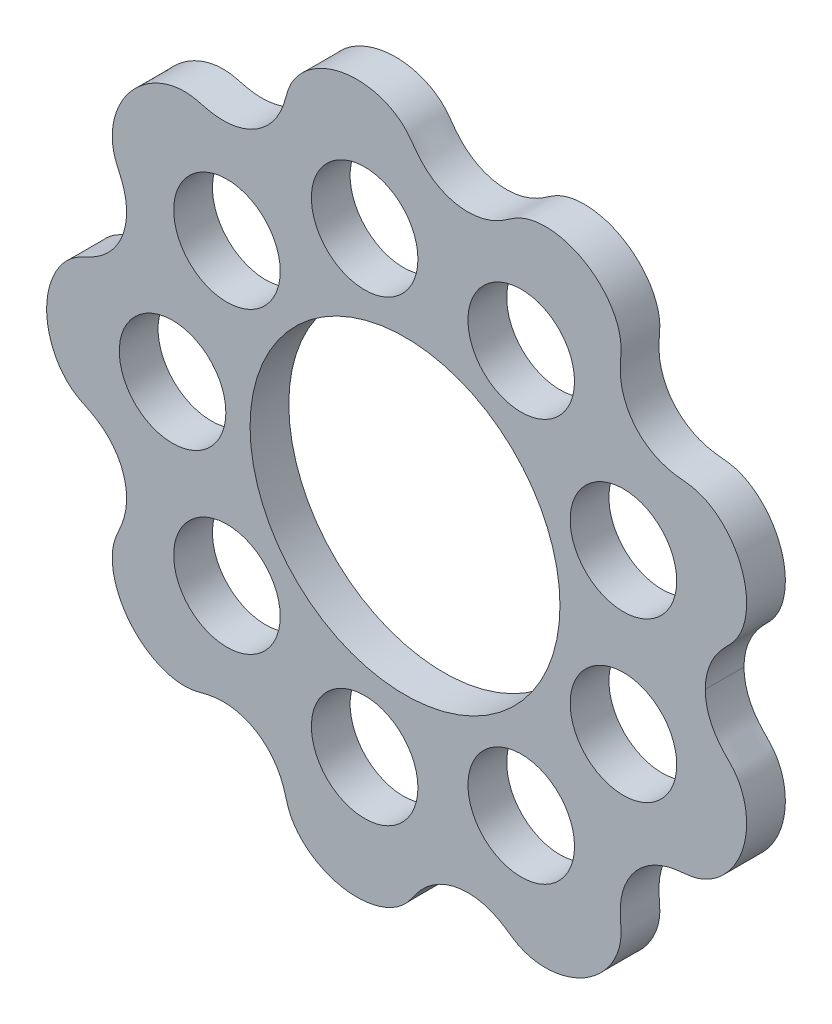
SolidWorks part; units mm, degrees
ref_plane "Front Plane" through (0, 0, 0) normal (0, 0, 1) x (1, 0, 0)
ref_plane "Top Plane" through (0, 0, 0) normal (0, 1, 0) x (1, 0, 0)
ref_plane "Right Plane" through (0, 0, 0) normal (1, 0, 0) x (0, 0, -1)
sketch "Sketch7" plane through (0, 0, 0) normal (0, 0, 1) x (1, 0, 0)
  line L0 (0, 0) -> (258.0103, 0) construction
  line L1 (0, 0) -> (-347.0754, 0) construction
  spline S0 degree 4 poles (196.3483, 108.0758) (197.1662, 107.7015) (198.778, 106.9006) (201.1195, 105.5525) (204.0762, 103.4954) (206.7877, 101.2641) (209.2605, 98.9001) (211.503, 96.4376) (213.5249, 93.9052) (215.3821, 91.2497) (217.0703, 88.4838) (218.5853, 85.6194) (219.9229, 82.6681) (221.0602, 79.6907) (222.003, 76.702) (222.7576, 73.7152) (223.3304, 70.7423) (223.7308, 67.7413) (223.9552, 64.7219) (223.9996, 61.6945) (223.8598, 58.6699) (223.5696, 56.0097) (223.1921, 53.7173) (222.783, 51.7892) (222.3895, 50.2186) (221.9941, 48.858) (221.6182, 47.7036) (221.2797, 46.7498) (220.9941, 45.993) (220.6924, 45.2405) (220.377, 44.4977) (220.0843, 43.8479) (219.8279, 43.3034) (219.6071, 42.8518) (219.4147, 42.4703) (219.2115, 42.0778) (219.0716, 41.8144) (218.8594, 41.4245) (218.6498, 41.0493) (218.3978, 40.6118) (218.0874, 40.0918) (217.7086, 39.4834) (217.2627, 38.8049) (216.6832, 37.967) (215.9566, 36.9862) (215.1906, 36.034) (214.3907, 35.1115) (213.5686, 34.2083) (212.7288, 33.3218) (211.6778, 32.2439) (210.4271, 30.9635) (209.1393, 29.6063) (207.8338, 28.1552) (206.5772, 26.6614) (205.3778, 25.1212) (203.9577, 23.1367) (202.1969, 20.3552) (200.2855, 16.6739) (198.509, 11.9966) (197.2707, 6.7748) (196.7213, 1.3707) (196.9019, -4.124) (197.8374, -9.6059) (199.5327, -14.9676) (201.8262, -19.826) (204.5608, -24.1527) (207.2252, -27.5153) (209.5587, -30.0722) (211.5717, -32.1369) (213.1859, -33.7849) (214.8311, -35.5744) (216.4348, -37.5641) (217.9456, -39.7769) (219.3315, -42.2124) (220.5751, -44.8497) (221.6559, -47.6802) (222.7868, -51.4735) (223.6704, -56.0526) (224.098, -61.2886) (223.8814, -67.1221) (223.0682, -72.6713) (221.677, -78.0878) (219.7348, -83.3148) (217.2672, -88.2976) (214.2996, -92.9815) (210.7379, -97.4562) (206.5556, -101.6114) (202.4235, -104.7775) (198.5463, -107.0752) (195.249, -108.6051) (192.6562, -109.5774) (190.1082, -110.3052) (187.6288, -110.8071) (185.2415, -111.1288) (182.9644, -111.3553) (180.1178, -111.6366) (176.7125, -112.0775) (172.5437, -112.9078) (167.7045, -114.4113) (162.8565, -116.5886) (158.1326, -119.5183) (153.7882, -123.1085) (149.9308, -127.3239) (146.6665, -132.1027) (144.0877, -137.3639) (142.3641, -142.6719) (141.5004, -147.2973) (141.1638, -151.1128) (141.0952, -154.0727) (141.1438, -156.4406) (141.2772, -158.8048) (141.4604, -161.1653) (141.6432, -163.6629) (141.7144, -166.3045) (141.5688, -169.0815) (141.163, -171.9703) (140.5085, -174.8691) (139.6111, -177.7595) (138.1886, -181.3538) (136.0869, -185.4458) (133.1724, -189.8479) (129.3079, -194.3759) (125.0352, -198.3609) (120.3956, -201.8145) (115.4621, -204.7192) (110.3018, -207.0604) (104.9778, -208.8248) (99.2704, -210.051) (93.2273, -210.6147) (87.8589, -210.4043) (83.2549, -209.6499) (79.6559, -208.6688) (77.0167, -207.7267) (74.5752, -206.6229) (72.3373, -205.3889) (70.2893, -204.0793) (68.386, -202.7757) (66.003, -201.1518) (63.0796, -199.2978) (59.3053, -197.258) (54.5692, -195.3164) (49.3861, -193.9017) (43.8113, -193.1635) (38.1339, -193.1952) (32.4627, -194.0265) (26.9186, -195.6651) (21.6198, -198.0958) (16.9479, -201.0962) (13.3651, -204.1091) (10.6954, -206.8284) (8.7694, -209.0571) (7.3056, -210.9033) (5.9048, -212.7975) (4.5376, -214.7156) (3.0705, -216.7299) (1.4139, -218.7721) (-0.9968, -221.3003) (-3.833, -223.6597) (-6.9484, -225.732) (-10.9856, -227.8771) (-15.2158, -229.6243) (-20.2604, -231.0877) (-26.1062, -232.0402) (-31.9126, -232.322) (-37.6818, -231.9664) (-43.3464, -230.9977) (-48.8437, -229.4387) (-54.1122, -227.3119) (-59.2511, -224.5465) (-63.5105, -221.5561) (-66.9451, -218.5451) (-69.5861, -215.739) (-71.4705, -213.4163) (-73.1306, -211.0208) (-74.5612, -208.5695) (-75.7296, -206.1219) (-76.6525, -203.7073) (-77.3797, -201.3604) (-78.0037, -199.1159) (-78.7968, -196.3138) (-79.8668, -192.9854) (-81.4855, -188.962) (-83.9257, -184.3956) (-87.0646, -179.9541) (-90.9558, -175.794) (-95.405, -172.1987) (-100.3352, -169.2511) (-105.6494, -167.0216) (-111.2422, -165.5588) (-116.7175, -164.9186) (-121.3694, -164.9681) (-125.1409, -165.3653) (-128.0376, -165.8546) (-130.3367, -166.3409) (-132.619, -166.8992) (-134.8928, -167.4898) (-137.3043, -168.0747) (-139.8763, -168.5467) (-142.6103, -168.8236) (-145.4892, -168.869) (-148.4275, -168.6793) (-151.4071, -168.2542) (-155.1775, -167.425) (-159.5393, -166.0121) (-164.3222, -163.8631) (-169.3723, -160.8195) (-173.9463, -157.3111) (-178.0891, -153.3469) (-181.7654, -148.9865) (-184.9419, -144.286) (-187.5859, -139.3004) (-189.7509, -133.8536) (-191.0996, -128.7619) (-191.7929, -124.1462) (-191.9886, -120.1934) (-191.9091, -117.1588) (-191.6081, -114.2473) (-191.1007, -111.4747) (-190.3939, -108.8586) (-189.5171, -106.4111) (-188.5348, -104.1241) (-187.5461, -101.9602) (-186.3383, -99.2422) (-185.2405, -96.4767) (-184.3116, -93.6482) (-183.3737, -89.9761) (-182.684, -86.0219) (-182.3651, -81.1934) (-182.7627, -75.5487) (-183.938, -69.9985) (-185.8793, -64.6522) (-188.5525, -59.6205) (-191.905, -55.0019) (-195.6776, -51.0745) (-199.7053, -47.8158) (-203.3549, -45.4735) (-206.425, -43.8097) (-209.0363, -42.5284) (-211.1372, -41.5286) (-213.3346, -40.4328) (-215.578, -39.1479) (-217.8187, -37.6154) (-220.0221, -35.8197) (-222.1511, -33.7841) (-224.1848, -31.5124) (-226.1025, -29.0103) (-227.8835, -26.2852) (-229.7601, -22.9089) (-231.5901, -18.8273) (-233.2042, -14.0062) (-234.4061, -8.4431) (-234.9403, -3.3833) (-235.0023, 1.0977) (-234.7605, 4.9666) (-234.3559, 8.2155) (-233.7506, 11.4331) (-232.9447, 14.6065) (-232.0637, 17.3326) (-231.1829, 19.6242) (-230.365, 21.4989) (-229.6604, 22.9756) (-228.5223, 25.1637) (-227.3608, 27.1086) (-226.2071, 28.8183) (-225.0895, 30.3031) (-224.58, 30.9531) (-224.0576, 31.5928) (-223.5892, 32.1432) (-223.1797, 32.608) (-222.8331, 32.9906) (-222.5527, 33.2936) (-222.2691, 33.5936) (-221.9818, 33.8911) (-221.6911, 34.1856) (-221.401, 34.4735) (-221.1441, 34.7228) (-220.9093, 34.9459) (-220.6673, 35.1724) (-220.455, 35.3683) (-220.288, 35.5202) (-220.0043, 35.7733) (-219.652, 36.0822) (-219.2802, 36.3982) (-218.8467, 36.7549) (-218.4025, 37.1088) (-217.9547, 37.4535) (-217.5008, 37.791) (-216.9265, 38.2034) (-216.2264, 38.6828) (-215.3942, 39.219) (-214.4236, 39.8002) (-213.4357, 40.3516) (-212.4337, 40.8768) (-211.4216, 41.3821) (-210.4038, 41.8757) (-209.1293, 42.4881) (-207.6031, 43.2297) (-205.907, 44.0942) (-204.0596, 45.1151) (-202.3174, 46.1659) (-200.6815, 47.2431) (-198.6949, 48.6739) (-196.4135, 50.5273) (-193.4298, 53.3506) (-190.5677, 56.7603) (-188.191, 60.3424) (-186.287, 64.022) (-185.0077, 67.0831) (-183.982, 70.2409) (-183.2171, 73.4746) (-182.7136, 76.7916) (-182.4818, 80.1709) (-182.5297, 83.5899) (-182.8617, 87.0253) (-183.3171, 89.5733) (-183.7077, 91.2528) (-183.9238, 92.0871) knots 0 0 0 0 0 0.003476 0.006953 0.010429 0.013906 0.017035 0.020164 0.023293 0.026422 0.029551 0.03268 0.035809 0.038938 0.041862 0.044785 0.047709 0.050633 0.053557 0.05648 0.059404 0.062328 0.063892 0.065456 0.06702 0.068585 0.069367 0.070149 0.070931 0.071713 0.072495 0.073277 0.073668 0.074059 0.07445 0.074841 0.075235 0.075628 0.076021 0.076415 0.077201 0.077988 0.078774 0.079561 0.081134 0.082707 0.083494 0.08428 0.085854 0.087427 0.089313 0.091198 0.093084 0.09497 0.096856 0.098741 0.102513 0.107684 0.112856 0.118026 0.123196 0.128618 0.13404 0.139452 0.144863 0.149321 0.15378 0.156009 0.158238 0.160467 0.162696 0.1654 0.168105 0.17081 0.173515 0.17666 0.179804 0.186094 0.191503 0.196912 0.202321 0.20773 0.213077 0.218425 0.223773 0.22912 0.235138 0.241155 0.243828 0.246501 0.249174 0.251847 0.254058 0.256269 0.25848 0.260692 0.265114 0.269536 0.274886 0.280235 0.285596 0.290956 0.296601 0.302247 0.307886 0.313525 0.318101 0.320388 0.322676 0.324964 0.327252 0.329539 0.331827 0.334642 0.337458 0.340273 0.343088 0.346116 0.349144 0.355199 0.360833 0.366467 0.3721 0.377734 0.383143 0.388552 0.393961 0.39937 0.40566 0.41195 0.414654 0.417359 0.420064 0.422769 0.424998 0.427227 0.429456 0.431685 0.436144 0.440602 0.446014 0.451426 0.456848 0.46227 0.467888 0.473506 0.479116 0.484726 0.489278 0.491555 0.493831 0.496107 0.498383 0.500659 0.502935 0.505737 0.508539 0.514142 0.517155 0.520167 0.526192 0.531797 0.537403 0.543008 0.548614 0.554093 0.559572 0.565051 0.57053 0.576601 0.579636 0.582671 0.585411 0.58815 0.59089 0.593629 0.59588 0.598132 0.600383 0.602634 0.607136 0.611638 0.617119 0.6226 0.628092 0.633585 0.639156 0.644727 0.650291 0.655855 0.660395 0.662665 0.664935 0.667205 0.669475 0.671745 0.674016 0.676794 0.679573 0.682352 0.685131 0.688163 0.691195 0.697259 0.702818 0.708377 0.713935 0.719494 0.724936 0.730379 0.735821 0.741263 0.747544 0.750684 0.753824 0.756544 0.759265 0.761986 0.764706 0.767005 0.769304 0.771603 0.773902 0.7785 0.780799 0.783098 0.788544 0.793991 0.799445 0.8049 0.810401 0.815903 0.821395 0.826888 0.831384 0.835881 0.838129 0.840377 0.842626 0.844874 0.847618 0.850361 0.853105 0.855848 0.858991 0.862134 0.865277 0.86842 0.873908 0.879397 0.884885 0.890374 0.893536 0.896697 0.899858 0.90302 0.906181 0.909343 0.910924 0.912504 0.914085 0.915666 0.920454 0.921252 0.92205 0.922848 0.923646 0.924444 0.924843 0.925242 0.925641 0.92604 0.926439 0.926838 0.927237 0.927636 0.927836 0.928035 0.928434 0.928707 0.928981 0.929527 0.930074 0.93062 0.931167 0.931713 0.93226 0.932806 0.933899 0.934992 0.936085 0.937178 0.938271 0.939364 0.940457 0.94155 0.943736 0.945922 0.947814 0.949706 0.951598 0.95349 0.957274 0.961058 0.967452 0.970649 0.973846 0.977054 0.980261 0.983468 0.986675 0.990006 0.993338 0.996669 1 1 1 1 1 construction
  spline S1 degree 4 poles (196.85, 0) (196.85, -0.3111) (196.8675, -2.0251) (197.0751, -5.1391) (197.8374, -9.6059) (199.5327, -14.9676) (201.8262, -19.826) (204.5608, -24.1527) (207.2252, -27.5153) (209.5587, -30.0722) (211.5717, -32.1369) (213.1859, -33.7849) (214.8311, -35.5744) (216.4348, -37.5641) (217.9456, -39.7769) (219.3315, -42.2124) (220.5751, -44.8497) (221.6559, -47.6802) (222.7868, -51.4735) (223.6704, -56.0526) (224.098, -61.2886) (223.8814, -67.1221) (223.0682, -72.6713) (221.677, -78.0878) (219.7348, -83.3148) (217.2672, -88.2976) (214.2996, -92.9815) (210.7379, -97.4562) (206.5556, -101.6114) (202.4235, -104.7775) (198.5463, -107.0752) (195.249, -108.6051) (192.6562, -109.5774) (190.1082, -110.3052) (187.6288, -110.8071) (185.2415, -111.1288) (182.9644, -111.3553) (180.1178, -111.6366) (176.7125, -112.0775) (172.5437, -112.9078) (167.7045, -114.4113) (162.8565, -116.5886) (158.1326, -119.5183) (153.7882, -123.1085) (149.9308, -127.3239) (146.6665, -132.1027) (144.0877, -137.3639) (142.3641, -142.6719) (141.5004, -147.2973) (141.1638, -151.1128) (141.0952, -154.0727) (141.1438, -156.4406) (141.2772, -158.8048) (141.4604, -161.1653) (141.6432, -163.6629) (141.7144, -166.3045) (141.5688, -169.0815) (141.163, -171.9703) (140.5085, -174.8691) (139.6111, -177.7595) (138.1886, -181.3538) (136.0869, -185.4458) (133.1724, -189.8479) (129.3079, -194.3759) (125.0352, -198.3609) (120.3956, -201.8145) (115.4621, -204.7192) (110.3018, -207.0604) (104.9778, -208.8248) (99.2704, -210.051) (93.2273, -210.6147) (87.8589, -210.4043) (83.2549, -209.6499) (79.6559, -208.6688) (77.0167, -207.7267) (74.5752, -206.6229) (72.3373, -205.3889) (70.2893, -204.0793) (68.386, -202.7757) (66.003, -201.1518) (63.0796, -199.2978) (59.3053, -197.258) (54.5692, -195.3164) (49.3861, -193.9017) (43.8113, -193.1635) (38.1339, -193.1952) (32.4627, -194.0265) (26.9186, -195.6651) (21.6198, -198.0958) (16.9479, -201.0962) (13.3651, -204.1091) (10.6954, -206.8284) (8.7694, -209.0571) (7.3056, -210.9033) (5.9048, -212.7975) (4.5376, -214.7156) (3.0705, -216.7299) (1.4139, -218.7721) (-0.9968, -221.3003) (-3.833, -223.6597) (-6.9484, -225.732) (-10.9856, -227.8771) (-15.2158, -229.6243) (-20.2604, -231.0877) (-26.1062, -232.0402) (-31.9126, -232.322) (-37.6818, -231.9664) (-43.3464, -230.9977) (-48.8437, -229.4387) (-54.1122, -227.3119) (-59.2511, -224.5465) (-63.5105, -221.5561) (-66.9451, -218.5451) (-69.5861, -215.739) (-71.4705, -213.4163) (-73.1306, -211.0208) (-74.5612, -208.5695) (-75.7296, -206.1219) (-76.6525, -203.7073) (-77.3797, -201.3604) (-78.0037, -199.1159) (-78.7968, -196.3138) (-79.8668, -192.9854) (-81.4855, -188.962) (-83.9257, -184.3956) (-87.0646, -179.9541) (-90.9558, -175.794) (-95.405, -172.1987) (-100.3352, -169.2511) (-105.6494, -167.0216) (-111.2422, -165.5588) (-116.7175, -164.9186) (-121.3694, -164.9681) (-125.1409, -165.3653) (-128.0376, -165.8546) (-130.3367, -166.3409) (-132.619, -166.8992) (-134.8928, -167.4898) (-137.3043, -168.0747) (-139.8763, -168.5467) (-142.6103, -168.8236) (-145.4892, -168.869) (-148.4275, -168.6793) (-151.4071, -168.2542) (-155.1775, -167.425) (-159.5393, -166.0121) (-164.3222, -163.8631) (-169.3723, -160.8195) (-173.9463, -157.3111) (-178.0891, -153.3469) (-181.7654, -148.9865) (-184.9419, -144.286) (-187.5859, -139.3004) (-189.7509, -133.8536) (-191.0996, -128.7619) (-191.7929, -124.1462) (-191.9886, -120.1934) (-191.9091, -117.1588) (-191.6081, -114.2473) (-191.1007, -111.4747) (-190.3939, -108.8586) (-189.5171, -106.4111) (-188.5348, -104.1241) (-187.5461, -101.9602) (-186.3383, -99.2422) (-185.2405, -96.4767) (-184.3116, -93.6482) (-183.3737, -89.9761) (-182.684, -86.0219) (-182.3651, -81.1934) (-182.7627, -75.5487) (-183.938, -69.9985) (-185.8793, -64.6522) (-188.5525, -59.6205) (-191.905, -55.0019) (-195.6776, -51.0745) (-199.7053, -47.8158) (-203.3549, -45.4735) (-206.425, -43.8097) (-209.0363, -42.5284) (-211.1372, -41.5286) (-213.3346, -40.4328) (-215.578, -39.1479) (-217.8187, -37.6154) (-220.0221, -35.8197) (-222.1511, -33.7841) (-224.1848, -31.5124) (-226.1025, -29.0103) (-227.8835, -26.2852) (-229.7601, -22.9089) (-231.5901, -18.8273) (-233.2042, -14.0062) (-234.4029, -8.4583) (-234.851, -4.2292) (-234.95, -1.4046) (-234.95, 0) knots 0.121994 0.121994 0.121994 0.121994 0.121994 0.123196 0.128618 0.13404 0.139452 0.144863 0.149321 0.15378 0.156009 0.158238 0.160467 0.162696 0.1654 0.168105 0.17081 0.173515 0.17666 0.179804 0.186094 0.191503 0.196912 0.202321 0.20773 0.213077 0.218425 0.223773 0.22912 0.235138 0.241155 0.243828 0.246501 0.249174 0.251847 0.254058 0.256269 0.25848 0.260692 0.265114 0.269536 0.274886 0.280235 0.285596 0.290956 0.296601 0.302247 0.307886 0.313525 0.318101 0.320388 0.322676 0.324964 0.327252 0.329539 0.331827 0.334642 0.337458 0.340273 0.343088 0.346116 0.349144 0.355199 0.360833 0.366467 0.3721 0.377734 0.383143 0.388552 0.393961 0.39937 0.40566 0.41195 0.414654 0.417359 0.420064 0.422769 0.424998 0.427227 0.429456 0.431685 0.436144 0.440602 0.446014 0.451426 0.456848 0.46227 0.467888 0.473506 0.479116 0.484726 0.489278 0.491555 0.493831 0.496107 0.498383 0.500659 0.502935 0.505737 0.508539 0.514142 0.517155 0.520167 0.526192 0.531797 0.537403 0.543008 0.548614 0.554093 0.559572 0.565051 0.57053 0.576601 0.579636 0.582671 0.585411 0.58815 0.59089 0.593629 0.59588 0.598132 0.600383 0.602634 0.607136 0.611638 0.617119 0.6226 0.628092 0.633585 0.639156 0.644727 0.650291 0.655855 0.660395 0.662665 0.664935 0.667205 0.669475 0.671745 0.674016 0.676794 0.679573 0.682352 0.685131 0.688163 0.691195 0.697259 0.702818 0.708377 0.713935 0.719494 0.724936 0.730379 0.735821 0.741263 0.747544 0.750684 0.753824 0.756544 0.759265 0.761986 0.764706 0.767005 0.769304 0.771603 0.773902 0.7785 0.780799 0.783098 0.788544 0.793991 0.799445 0.8049 0.810401 0.815903 0.821395 0.826888 0.831384 0.835881 0.838129 0.840377 0.842626 0.844874 0.847618 0.850361 0.853105 0.855848 0.858991 0.862134 0.865277 0.86842 0.873908 0.879397 0.884885 0.890314 0.890314 0.890314 0.890314 0.890314
  spline S2 degree 4 poles (196.85, 0) (196.85, 0.3111) (196.8675, 2.0251) (197.0751, 5.1391) (197.8374, 9.6059) (199.5327, 14.9676) (201.8262, 19.826) (204.5608, 24.1527) (207.2252, 27.5153) (209.5587, 30.0722) (211.5717, 32.1369) (213.1859, 33.7849) (214.8311, 35.5744) (216.4348, 37.5641) (217.9456, 39.7769) (219.3315, 42.2124) (220.5751, 44.8497) (221.6559, 47.6802) (222.7868, 51.4735) (223.6704, 56.0526) (224.098, 61.2886) (223.8814, 67.1221) (223.0682, 72.6713) (221.677, 78.0878) (219.7348, 83.3148) (217.2672, 88.2976) (214.2996, 92.9815) (210.7379, 97.4562) (206.5556, 101.6114) (202.4235, 104.7775) (198.5463, 107.0752) (195.249, 108.6051) (192.6562, 109.5774) (190.1082, 110.3052) (187.6288, 110.8071) (185.2415, 111.1288) (182.9644, 111.3553) (180.1178, 111.6366) (176.7125, 112.0775) (172.5437, 112.9078) (167.7045, 114.4113) (162.8565, 116.5886) (158.1326, 119.5183) (153.7882, 123.1085) (149.9308, 127.3239) (146.6665, 132.1027) (144.0877, 137.3639) (142.3641, 142.6719) (141.5004, 147.2973) (141.1638, 151.1128) (141.0952, 154.0727) (141.1438, 156.4406) (141.2772, 158.8048) (141.4604, 161.1653) (141.6432, 163.6629) (141.7144, 166.3045) (141.5688, 169.0815) (141.163, 171.9703) (140.5085, 174.8691) (139.6111, 177.7595) (138.1886, 181.3538) (136.0869, 185.4458) (133.1724, 189.8479) (129.3079, 194.3759) (125.0352, 198.3609) (120.3956, 201.8145) (115.4621, 204.7192) (110.3018, 207.0604) (104.9778, 208.8248) (99.2704, 210.051) (93.2273, 210.6147) (87.8589, 210.4043) (83.2549, 209.6499) (79.6559, 208.6688) (77.0167, 207.7267) (74.5752, 206.6229) (72.3373, 205.3889) (70.2893, 204.0793) (68.386, 202.7757) (66.003, 201.1518) (63.0796, 199.2978) (59.3053, 197.258) (54.5692, 195.3164) (49.3861, 193.9017) (43.8113, 193.1635) (38.1339, 193.1952) (32.4627, 194.0265) (26.9186, 195.665) (21.6198, 198.0958) (16.9479, 201.0962) (13.3651, 204.1091) (10.6954, 206.8284) (8.7694, 209.0571) (7.3056, 210.9033) (5.9048, 212.7975) (4.5376, 214.7156) (3.0705, 216.7299) (1.4139, 218.7721) (-0.9968, 221.3003) (-3.833, 223.6597) (-6.9484, 225.732) (-10.9856, 227.8771) (-15.2158, 229.6243) (-20.2604, 231.0877) (-26.1062, 232.0402) (-31.9126, 232.322) (-37.6818, 231.9664) (-43.3464, 230.9977) (-48.8437, 229.4387) (-54.1122, 227.3119) (-59.2511, 224.5465) (-63.5105, 221.5561) (-66.9451, 218.5451) (-69.5861, 215.739) (-71.4705, 213.4163) (-73.1306, 211.0208) (-74.5612, 208.5695) (-75.7296, 206.1219) (-76.6525, 203.7073) (-77.3797, 201.3604) (-78.0037, 199.1159) (-78.7968, 196.3138) (-79.8668, 192.9854) (-81.4855, 188.962) (-83.9257, 184.3956) (-87.0646, 179.9541) (-90.9558, 175.794) (-95.405, 172.1987) (-100.3352, 169.2511) (-105.6494, 167.0216) (-111.2422, 165.5588) (-116.7175, 164.9186) (-121.3694, 164.9681) (-125.1409, 165.3653) (-128.0376, 165.8546) (-130.3367, 166.3409) (-132.619, 166.8992) (-134.8928, 167.4898) (-137.3043, 168.0747) (-139.8763, 168.5467) (-142.6103, 168.8236) (-145.4892, 168.869) (-148.4275, 168.6793) (-151.4071, 168.2542) (-155.1775, 167.425) (-159.5393, 166.0121) (-164.3222, 163.8631) (-169.3723, 160.8195) (-173.9463, 157.3111) (-178.0891, 153.3469) (-181.7654, 148.9865) (-184.9419, 144.286) (-187.5859, 139.3004) (-189.7509, 133.8536) (-191.0996, 128.7619) (-191.7929, 124.1462) (-191.9886, 120.1934) (-191.9091, 117.1588) (-191.6081, 114.2473) (-191.1007, 111.4747) (-190.3939, 108.8586) (-189.5171, 106.4111) (-188.5348, 104.1241) (-187.5461, 101.9602) (-186.3383, 99.2422) (-185.2405, 96.4767) (-184.3116, 93.6482) (-183.3737, 89.9761) (-182.684, 86.0219) (-182.3651, 81.1934) (-182.7627, 75.5487) (-183.938, 69.9985) (-185.8793, 64.6522) (-188.5525, 59.6205) (-191.905, 55.0019) (-195.6776, 51.0745) (-199.7053, 47.8157) (-203.3549, 45.4735) (-206.425, 43.8097) (-209.0363, 42.5284) (-211.1372, 41.5286) (-213.3346, 40.4328) (-215.578, 39.1479) (-217.8187, 37.6154) (-220.0221, 35.8197) (-222.1511, 33.7841) (-224.1848, 31.5124) (-226.1025, 29.0103) (-227.8835, 26.2852) (-229.7601, 22.9089) (-231.5901, 18.8273) (-233.2042, 14.0062) (-234.4029, 8.4583) (-234.851, 4.2292) (-234.95, 1.4046) (-234.95, 0) knots 0.121994 0.121994 0.121994 0.121994 0.121994 0.123196 0.128618 0.13404 0.139452 0.144863 0.149321 0.15378 0.156009 0.158238 0.160467 0.162696 0.1654 0.168105 0.17081 0.173515 0.17666 0.179804 0.186094 0.191503 0.196912 0.202321 0.20773 0.213077 0.218425 0.223773 0.22912 0.235138 0.241155 0.243828 0.246501 0.249174 0.251847 0.254058 0.256269 0.25848 0.260692 0.265114 0.269536 0.274886 0.280235 0.285596 0.290956 0.296601 0.302247 0.307886 0.313525 0.318101 0.320388 0.322676 0.324964 0.327252 0.329539 0.331827 0.334642 0.337458 0.340273 0.343088 0.346116 0.349144 0.355199 0.360833 0.366467 0.3721 0.377734 0.383143 0.388552 0.393961 0.39937 0.40566 0.41195 0.414654 0.417359 0.420064 0.422769 0.424998 0.427227 0.429456 0.431685 0.436144 0.440602 0.446014 0.451426 0.456848 0.46227 0.467888 0.473506 0.479116 0.484726 0.489278 0.491555 0.493831 0.496107 0.498383 0.500659 0.502935 0.505737 0.508539 0.514142 0.517155 0.520167 0.526192 0.531797 0.537403 0.543008 0.548614 0.554093 0.559572 0.565051 0.57053 0.576601 0.579636 0.582671 0.585411 0.58815 0.59089 0.593629 0.59588 0.598132 0.600383 0.602634 0.607136 0.611638 0.617119 0.6226 0.628092 0.633585 0.639156 0.644727 0.650291 0.655855 0.660395 0.662665 0.664935 0.667205 0.669475 0.671745 0.674016 0.676794 0.679573 0.682352 0.685131 0.688163 0.691195 0.697259 0.702818 0.708377 0.713935 0.719494 0.724936 0.730379 0.735821 0.741263 0.747544 0.750684 0.753824 0.756544 0.759265 0.761986 0.764706 0.767005 0.769304 0.771603 0.773902 0.7785 0.780799 0.783098 0.788544 0.793991 0.799445 0.8049 0.810401 0.815903 0.821395 0.826888 0.831384 0.835881 0.838129 0.840377 0.842626 0.844874 0.847618 0.850361 0.853105 0.855848 0.858991 0.862134 0.865277 0.86842 0.873908 0.879397 0.884885 0.890314 0.890314 0.890314 0.890314 0.890314
extrude "Boss-Extrude3" add sketch "Sketch7" along normal blind 25.4 contours S2 S1
sketch "Sketch8" plane through (0, 0, 25.4) normal (0, 0, 1) x (1, 0, 0)
  circle A0 centre (0, 0) radius 101.6
extrude "Cut-Extrude2" cut sketch "Sketch8" against normal through all contours A0
sketch "Sketch9" plane through (0, 0, 25.4) normal (0, 0, 1) x (1, 0, 0)
  line L0 (0, 0) -> (-318.0996, 0) construction
  circle A0 centre (0, 0) radius 152.4 construction
  circle A1 centre (-152.4, 0) radius 34.925
  circle A2 centre (-116.7452, 97.9608) radius 34.925
  circle A3 centre (-26.464, 150.0847) radius 34.925
  circle A4 centre (76.2, 131.9823) radius 34.925
  circle A5 centre (143.2092, 52.1239) radius 34.925
  circle A6 centre (143.2092, -52.1239) radius 34.925
  circle A7 centre (76.2, -131.9823) radius 34.925
  circle A8 centre (-26.464, -150.0847) radius 34.925
  circle A9 centre (-116.7452, -97.9608) radius 34.925
  point P24 (0, 0)
  dimension "D1" = 9
extrude "Cut-Extrude3" cut sketch "Sketch9" against normal through all
equation "\"R\"= 30mm"
equation "\"E\"= 1.5mm"
equation "\"Rr\"= 4mm"
equation "\"N\"= 8mm"
equation "\"RotorThickness\"= 7mm"
equation "\"PinDiameter\"= 5mm"
equation "\"OutputHoleDiameter\"= \"PinDiameter\" + \"E\""
equation "\"BoltCircle\" = 24mm"
equation "\"Lobes\"= \"N\" - 1"
